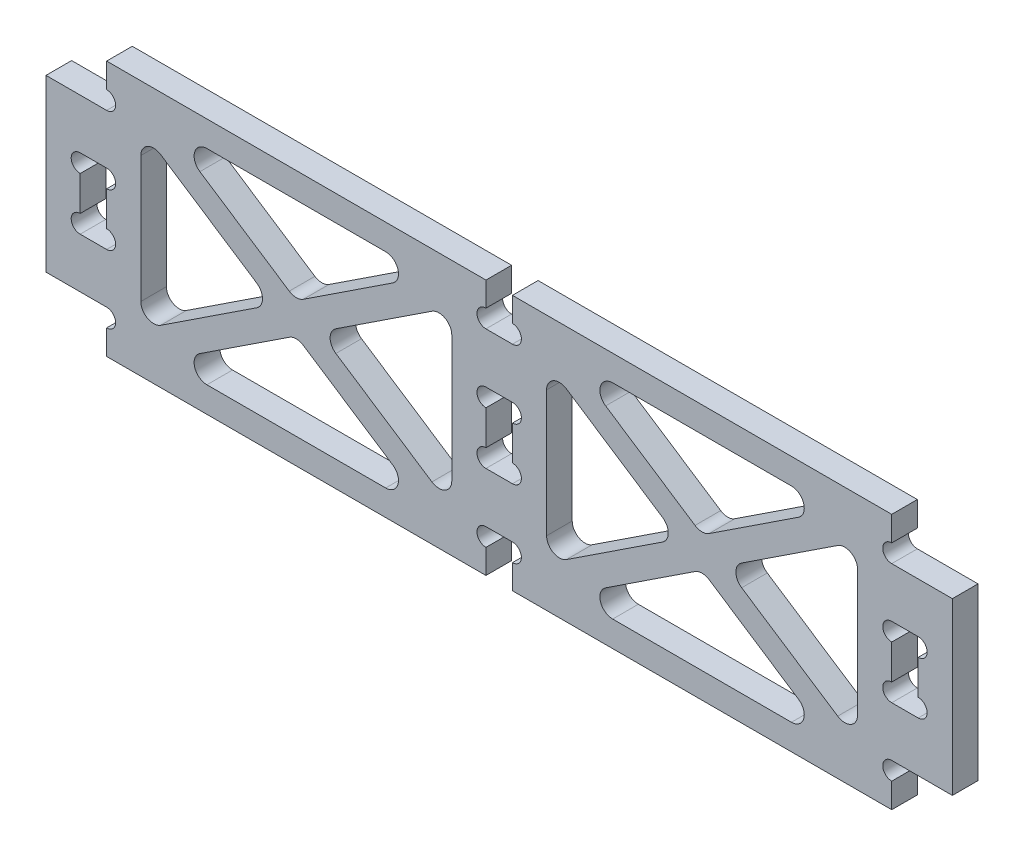
SolidWorks part; units mm, degrees
material "玻纤板"
ref_plane "前视基准面" through (0, 0, 0) normal (0, 0, 1) x (1, 0, 0)
ref_plane "上视基准面" through (0, 0, 0) normal (0, 1, 0) x (1, 0, 0)
ref_plane "右视基准面" through (0, 0, 0) normal (1, 0, 0) x (0, 0, -1)
sketch "草图1" plane through (0, 0, 0) normal (0, 0, 1) x (1, 0, 0)
  line L1 (1.55, -4.125) -> (-1.55, -4.125)
  line L2 (1.55, -4.125) -> (1.55, 4.125)
  line L3 (1.55, 4.125) -> (-1.55, 4.125)
  line L4 (-1.55, -4.125) -> (-1.55, 4.125)
  line L5 (1.55, -4.125) -> (-1.55, 4.125) construction
  line L6 (1.55, 4.125) -> (-1.55, -4.125) construction
  line L7 (96.55, -4.125) -> (93.45, -4.125)
  line L8 (96.55, -4.125) -> (96.55, 4.125)
  line L9 (96.55, 4.125) -> (93.45, 4.125)
  line L10 (93.45, -4.125) -> (93.45, 4.125)
  line L11 (96.55, -4.125) -> (93.45, 4.125) construction
  line L12 (96.55, 4.125) -> (93.45, -4.125) construction
  line L13 (100.55, 9.975) -> (100.55, -9.975)
  line L15 (-5.55, -9.975) -> (-5.55, 9.975)
  line L16 (-5.55, 9.975) -> (1.55, 9.975)
  line L17 (1.55, 9.975) -> (1.55, 14.975)
  line L20 (93.45, 14.975) -> (93.45, 9.975)
  line L21 (93.45, 9.975) -> (100.55, 9.975)
  line L22 (0, 0) -> (23.3109, 0) construction
  line L23 (93.45, -9.975) -> (100.55, -9.975)
  line L24 (93.45, -14.975) -> (93.45, -9.975)
  line L27 (1.55, -9.975) -> (1.55, -14.975)
  line L28 (-5.55, -9.975) -> (1.55, -9.975)
  line L29 (47.5, 10.025) -> (47.5, -10.025) construction
  line L30 (1.55, 14.975) -> (45.95, 14.975)
  line L34 (49.05, 14.975) -> (93.45, 14.975)
  line L38 (49.05, -14.975) -> (93.45, -14.975)
  line L39 (1.55, -14.975) -> (45.95, -14.975)
  line L40 (45.95, 14.975) -> (45.95, 10.025)
  line L41 (49.05, -4.125) -> (45.95, -4.125)
  line L42 (49.05, -4.125) -> (49.05, 4.125)
  line L43 (49.05, 4.125) -> (45.95, 4.125)
  line L44 (45.95, -4.125) -> (45.95, 4.125)
  line L45 (49.05, -4.125) -> (45.95, 4.125) construction
  line L46 (49.05, 4.125) -> (45.95, -4.125) construction
  line L47 (45.95, 10.025) -> (49.05, 10.025)
  line L48 (49.05, 10.025) -> (49.05, 14.975)
  line L49 (45.95, -10.025) -> (49.05, -10.025)
  line L50 (49.05, -10.025) -> (49.05, -14.975)
  line L51 (45.95, -14.975) -> (45.95, -10.025)
  line L52 (5.55, -10.1794) -> (21.021, 0)
  line L53 (41.95, -11.975) -> (5.55, -11.975) construction
  line L54 (41.95, -11.975) -> (41.95, 11.975) construction
  line L55 (41.95, 11.975) -> (5.55, 11.975) construction
  line L56 (5.55, -11.975) -> (5.55, 11.975) construction
  line L57 (41.95, -11.975) -> (5.55, 11.975) construction
  line L58 (41.95, 11.975) -> (5.55, -11.975) construction
  line L59 (8.279, -11.975) -> (23.75, -1.7956)
  line L60 (8.279, 11.975) -> (23.75, 1.7956)
  line L61 (5.55, 10.1794) -> (21.021, 0)
  line L62 (8.279, 11.975) -> (39.221, 11.975)
  line L63 (41.95, 10.1794) -> (41.95, -10.1794)
  line L64 (39.221, -11.975) -> (8.279, -11.975)
  line L65 (5.55, -10.1794) -> (5.55, 10.1794)
  line L66 (23.75, 1.7956) -> (39.221, 11.975)
  line L67 (26.479, 0) -> (41.95, -10.1794)
  line L68 (26.479, 0) -> (41.95, 10.1794)
  line L69 (23.75, -1.7956) -> (39.221, -11.975)
  line L70 (68.521, 0) -> (53.05, 10.1794)
  line L71 (68.521, 0) -> (53.05, -10.1794)
  line L72 (53.05, 10.1794) -> (53.05, -10.1794)
  line L73 (86.721, 11.975) -> (55.779, 11.975)
  line L74 (71.25, 1.7956) -> (55.779, 11.975)
  line L75 (86.721, 11.975) -> (71.25, 1.7956)
  line L76 (71.25, -1.7956) -> (55.779, -11.975)
  line L77 (86.721, -11.975) -> (71.25, -1.7956)
  line L78 (55.779, -11.975) -> (86.721, -11.975)
  line L79 (89.45, -10.1794) -> (89.45, 10.1794)
  line L80 (89.45, -10.1794) -> (73.979, 0)
  line L81 (89.45, 10.1794) -> (73.979, 0)
  circle A0 centre (1.55, 11.025) radius 1.05
  circle A1 centre (-1.55, 3.075) radius 1.05
  circle A2 centre (-1.55, -3.075) radius 1.05
  circle A3 centre (1.55, -3.075) radius 1.05
  circle A4 centre (1.55, 3.075) radius 1.05
  circle A5 centre (1.55, -11.025) radius 1.05
  circle A6 centre (93.45, -3.075) radius 1.05
  circle A7 centre (93.45, 3.075) radius 1.05
  circle A8 centre (93.45, 11.025) radius 1.05
  circle A9 centre (96.55, 3.075) radius 1.05
  circle A10 centre (96.55, -3.075) radius 1.05
  circle A11 centre (93.45, -11.025) radius 1.05
  circle A12 centre (45.95, 3.075) radius 1.05
  circle A13 centre (49.05, 3.075) radius 1.05
  circle A14 centre (49.05, -3.075) radius 1.05
  circle A15 centre (45.95, -3.075) radius 1.05
  circle A16 centre (45.95, -11.075) radius 1.05
  circle A17 centre (49.05, -11.075) radius 1.05
  circle A18 centre (45.95, 11.075) radius 1.05
  circle A19 centre (49.05, 11.075) radius 1.05
  point P0 (0, 0)
  point P6 (95, 0)
  point P17 (47.5, 0)
  point P81 (23.75, 0)
  dimension "D9" = 2.1
  dimension "D1" = 95
  dimension "D2" = 3.1
  dimension "D3" = 8.25
  dimension "D4" = 5.85
  dimension "D5" = 5
  dimension "D6" = 3.1
  dimension "D7" = 4
  dimension "D8" = 4
  dimension "D10" = 5.9
  dimension "D11" = 4
  dimension "D12" = 4
  dimension "D13" = 3
  dimension "D14" = 3
  dimension "D15" = 3
extrude "凸台-拉伸1" add sketch "草图1" along normal blind 3
fillet "圆角1" radius 1.5 24 edges at (73.979, 0, 1.5) (89.45, -10.1794, 1.5) (89.45, 10.1794, 1.5) (86.721, -11.975, 1.5) (71.25, -1.7956, 1.5) (55.779, -11.975, 1.5) (53.05, -10.1794, 1.5) (68.521, 0, 1.5) (53.05, 10.1794, 1.5) (39.221, 11.975, 1.5) (23.75, 1.7956, 1.5) (21.021, 0, 1.5) (5.55, 10.1794, 1.5) (5.55, -10.1794, 1.5) (41.95, -10.1794, 1.5) (41.95, 10.1794, 1.5) (26.479, 0, 1.5) (8.279, -11.975, 1.5) (39.221, -11.975, 1.5) (23.75, -1.7956, 1.5) (55.779, 11.975, 1.5) (71.25, 1.7956, 1.5) (86.721, 11.975, 1.5) (8.279, 11.975, 1.5)
